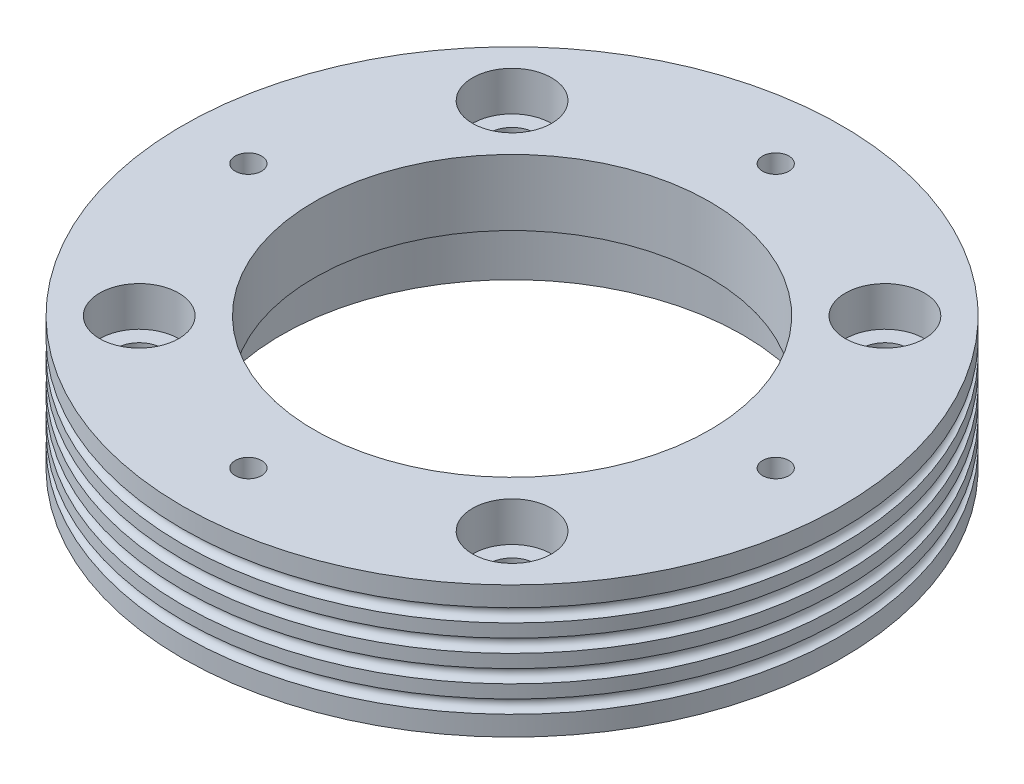
SolidWorks part; units mm, degrees
ref_plane "前视基准面" through (0, 0, 0) normal (0, 0, 1) x (1, 0, 0)
ref_plane "上视基准面" through (0, 0, 0) normal (0, 1, 0) x (1, 0, 0)
ref_plane "右视基准面" through (0, 0, 0) normal (1, 0, 0) x (0, 0, -1)
sketch "草图1" plane through (0, 0, 0) normal (0, 1, 0) x (1, 0, 0)
  circle A0 centre (0, 0) radius 25
  dimension "D1" = 50
extrude "凸台-拉伸1" add sketch "草图1" along normal blind 10
sketch "草图2" plane through (0, 10, 0) normal (0, 1, 0) x (1, 0, 0)
  circle A0 centre (0, 0) radius 20 construction
  point P3 (20, 0)
  point P4 (0, 20)
  point P5 (-20, 0)
  point P6 (0, -20)
  dimension "D1" = 40
hole_wizard "孔1" positions "草图2" profile "草图3" legacy end condition up to next
sketch "草图3" plane through (0, 10, 20) normal (1, 0, 0) x (0, 0, 1)
  line L0 (0, 0) -> (0, 10)
  line L1 (0, 10) -> (1, 10)
  line L2 (1, 10) -> (1, 0)
  line L3 (1, 0) -> (0, 0)
  line L4 (0, 110) -> (0, -10) construction
  dimension "直径" = 2
  dimension "深度" = 10
sketch "草图4" plane through (0, 0, 0) normal (0, -1, 0) x (1, 0, 0)
  circle A0 centre (0, 0) radius 17.5
  dimension "D1" = 35
extrude "切除-拉伸1" cut sketch "草图4" against normal blind 5
sketch "草图5" plane through (0, 5, 0) normal (0, -1, 0) x (1, 0, 0)
  circle A0 centre (0, 0) radius 15
  dimension "D1" = 30
extrude "切除-拉伸2" cut sketch "草图5" against normal blind 5
sketch "草图6" plane through (0, 10, 0) normal (0, 1, 0) x (1, 0, 0)
  line L0 (0, 0) -> (14.1421, 14.1421) construction
  line L2 (-5.5, 0) -> (5.5, 0) construction
  circle A0 centre (0, 0) radius 20 construction
  point P9 (14.1421, 14.1421)
  point P27 (14.1421, -14.1421)
  point P28 (-14.1421, -14.1421)
  point P29 (-14.1421, 14.1421)
  dimension "D1" = 40
  dimension "D2" = 45
  dimension "D3" = 4
hole_wizard "孔3" positions "草图6" profile "草图8" legacy end condition up to next
sketch "草图8" plane through (-14.1421, 10, -14.1421) normal (1, 0, 0) x (0, 0, 1)
  line L0 (0, 0) -> (0, 10)
  line L1 (0, 10) -> (1.75, 10)
  line L2 (1.75, 10) -> (1.75, 3)
  line L3 (1.75, 3) -> (3, 3)
  line L4 (3, 3) -> (3, 0)
  line L5 (3, 0) -> (0, 0)
  line L6 (0, 110) -> (0, -10) construction
  dimension "直径" = 3.5
  dimension "深度" = 10
  dimension "柱坑直径" = 6
  dimension "柱坑深度" = 3
ref_plane "基准面1" through (0, 2, 0) normal (0, 1, 0) x (1, 0, 0)
sketch "草图11" plane through (0, 2, 0) normal (0, 1, 0) x (1, 0, 0)
  circle A0 centre (0, 0) radius 25
  dimension "D1" = 50
sweep "切除-扫描1" cut path "草图11" circular profile diameter 1 parameters "D3"=1
pattern_linear "阵列(线性)1" count 4 spacing 2 along (0, 1, 0) of "切除-扫描1"
